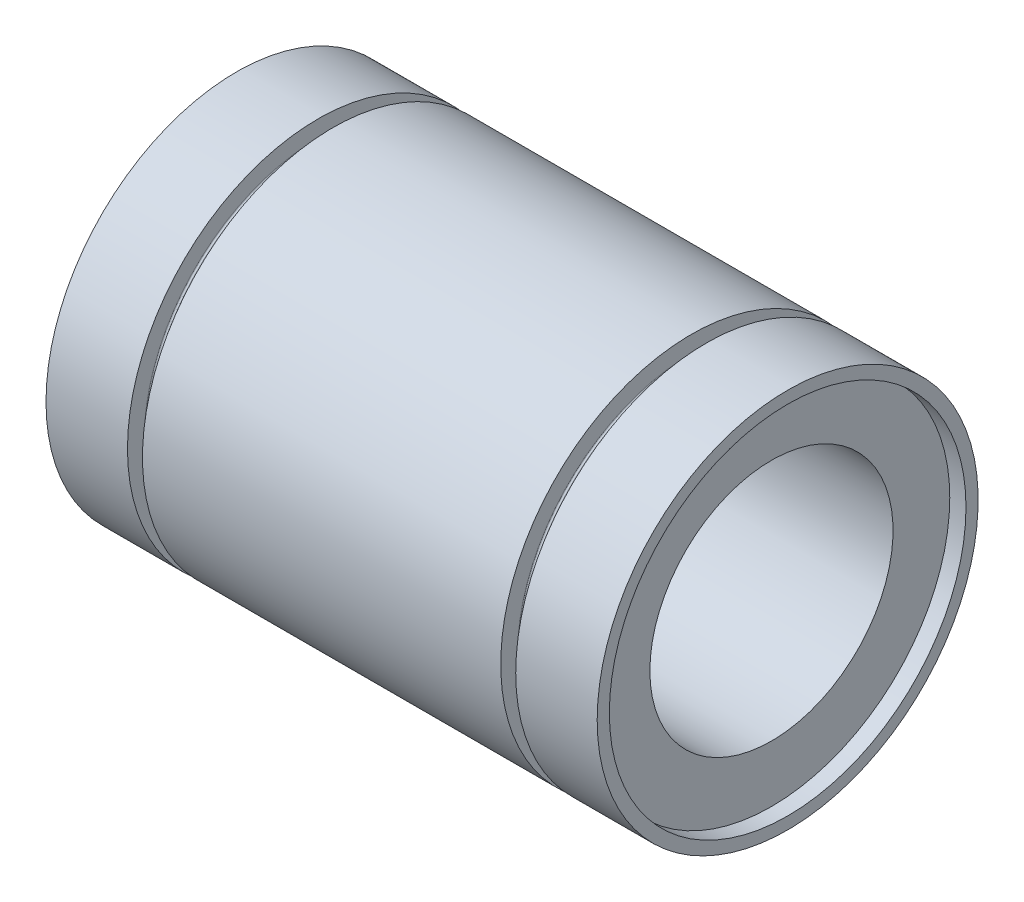
SolidWorks part; units mm, degrees
ref_plane "Front Plane" through (0, 0, 0) normal (0, 0, 1) x (1, 0, 0)
ref_plane "Top Plane" through (0, 0, 0) normal (0, 1, 0) x (1, 0, 0)
ref_plane "Right Plane" through (0, 0, 0) normal (1, 0, 0) x (0, 0, -1)
sketch "Sketch1" plane through (0, 0, 0) normal (0, 1, 0) x (1, 0, 0)
  line L0 (0, 15) -> (32, 15)
  line L1 (0, 0) -> (32, 0)
  line L2 (0, 0) -> (0, 23.5)
  line L3 (0, 23.5) -> (34, 23.5)
  line L4 (32, 0) -> (32, 15)
  line L5 (32, 15) -> (32, 22)
  line L6 (32, 22) -> (34, 22)
  line L7 (34, 22) -> (34, 23.5)
  line L8 (0, 23.5) -> (0, 44.3178) construction
  line L9 (32, 0) -> (58.5772, 0) construction
  dimension "D1" = 47
  dimension "D2" = 68
  dimension "D3" = 30
  dimension "D4" = 2
  dimension "D5" = 1.5
revolve "Revolve1" add sketch "Sketch1" angle 360 about L1
ref_plane "Plane1" through (0, 0, 0) normal (0, -1, 0) x (0, 0, 1)
ref_plane "Plane2" through (0, 0, 0) normal (0, -1, 0) x (0, 0, 1)
ref_plane "Plane3" through (0, 0, 0) normal (0, -1, 0) x (0, 0, 1)
sketch "Sketch7" plane through (0, 0, 0) normal (0, -1, 0) x (0, 0, 1)
  line L0 (21.435, -23.95) -> (28.2, -23.95)
  line L1 (28.2, -23.95) -> (28.2, -22.1)
  line L2 (28.2, -22.1) -> (21.435, -22.1)
  line L3 (21.25, -22.285) -> (21.25, -23.765)
  line L4 (0, -50) -> (0, 50) construction
  line L5 (23.5, -34) -> (23.5, 0) construction
  line L7 (23.5, 0) -> (-23.5, 0) construction
  arc A0 (21.25, -23.765) -> (21.435, -23.95) centre (21.435, -23.765) ccw
  arc A1 (21.25, -22.285) -> (21.435, -22.1) centre (21.435, -22.285) cw
  dimension "D1" = 0.185
  dimension "D2" = 0.185
  dimension "D3" = 2.25
  dimension "D4" = 1.85
  dimension "D5" = 22.1
revolve "Groove for DIN 471 - 45 x 1.75, Circlip for shafts - normal1" cut sketch "Sketch7"
mirror "Mirror2" about plane through (0, 0, 0) normal (-1, 0, 0) of bodies 106 103
